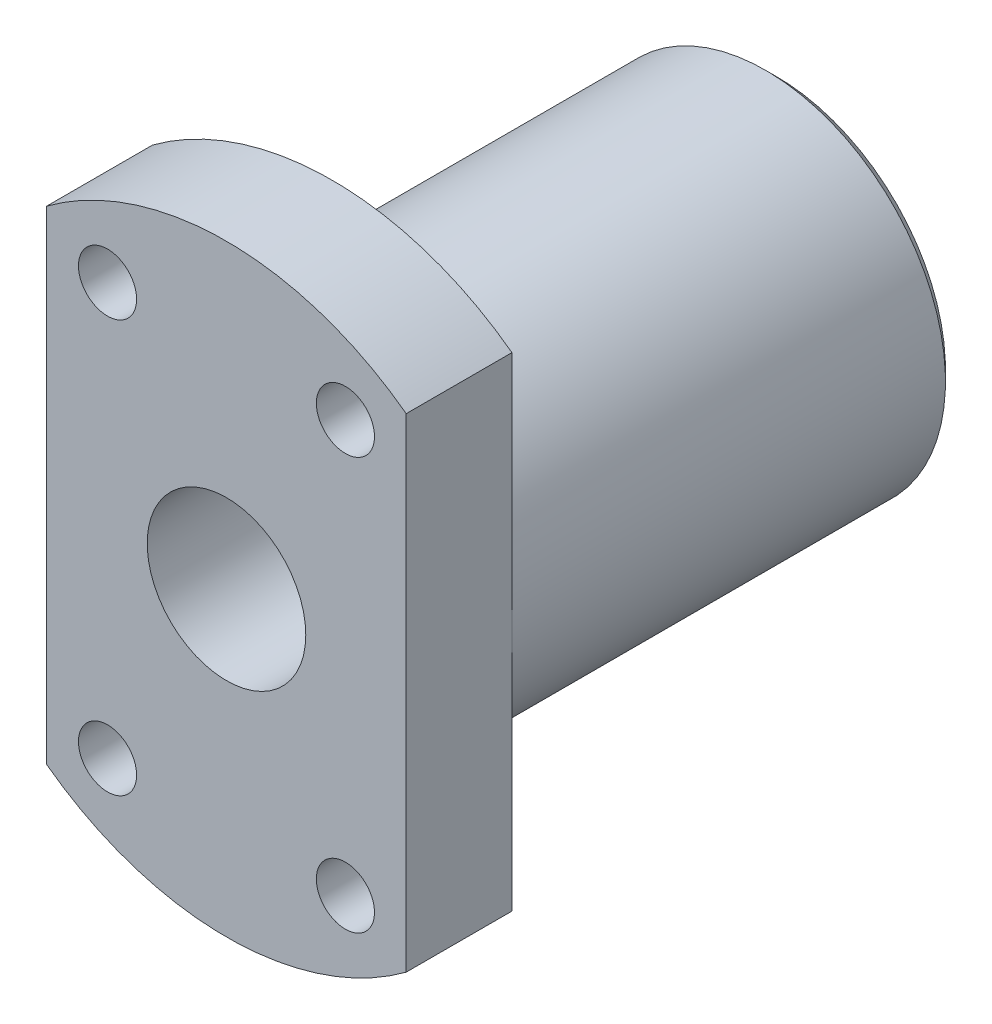
SolidWorks part; units mm, degrees
material "SKD11淬火HRC56-60"
ref_plane "前基準面" through (0, 0, 0) normal (0, 0, 1) x (1, 0, 0)
ref_plane "上基準面" through (0, 0, 0) normal (0, 1, 0) x (1, 0, 0)
ref_plane "右基準面" through (0, 0, 0) normal (1, 0, 0) x (0, 0, -1)
sketch "草图1" plane through (0, 0, 0) normal (0, 0, 1) x (1, 0, 0)
  circle A0 centre (0, 0) radius 28.5
  dimension "D1" = 57
extrude "凸台-拉伸1" add sketch "草图1" along normal blind 10
sketch "草图2" plane through (0, 0, 10) normal (0, 0, 1) x (1, 0, 0)
  line L0 (0, 0) -> (0, 35.3381) construction
  line L1 (-17, 37.2734) -> (-59.7807, 37.2734)
  line L2 (-17, 37.2734) -> (-17, -39.3077)
  line L3 (-17, -39.3077) -> (-59.7807, -39.3077)
  line L4 (-59.7807, 37.2734) -> (-59.7807, -39.3077)
  line L5 (59.7807, 37.2734) -> (59.7807, -39.3077)
  line L6 (17, -39.3077) -> (59.7807, -39.3077)
  line L7 (17, 37.2734) -> (17, -39.3077)
  line L8 (17, 37.2734) -> (59.7807, 37.2734)
  dimension "D1" = 34
extrude "切除-拉伸1" cut sketch "草图2" against normal through all
sketch "草图3" plane through (0, 0, 0) normal (0, 0, -1) x (-1, 0, 0)
  circle A0 centre (0, 0) radius 17
  dimension "D1" = 34
extrude "凸台-拉伸2" add sketch "草图3" along normal blind 42
sketch "草图4" plane through (0, 0, 0) normal (0, 0, -1) x (-1, 0, 0)
  line L0 (0, 0) -> (0, 34.4896) construction
  line L1 (0, 0) -> (-18.2878, 31.6754) construction
  line L2 (0, 0) -> (11.8371, 0) construction
  circle A0 centre (-11.25, 19.4856) radius 2.75
  circle A1 centre (0, 0) radius 22.5 construction
  circle A2 centre (11.25, 19.4856) radius 2.75
  circle A3 centre (11.25, -19.4856) radius 2.75
  circle A4 centre (-11.25, -19.4856) radius 2.75
  dimension "D2" = 45
  dimension "D3" = 5.5
  dimension "D1" = 30
extrude "切除-拉伸2" cut sketch "草图4" against normal blind 42
sketch "草图5" plane through (0, 0, 10) normal (0, 0, 1) x (1, 0, 0)
  circle A0 centre (0, 0) radius 7.5
  dimension "D1" = 15
extrude "切除-拉伸3" cut sketch "草图5" against normal through all
chamfer "倒角1" distance 1 angle 45 1 edges at (-17, 0, -42)
